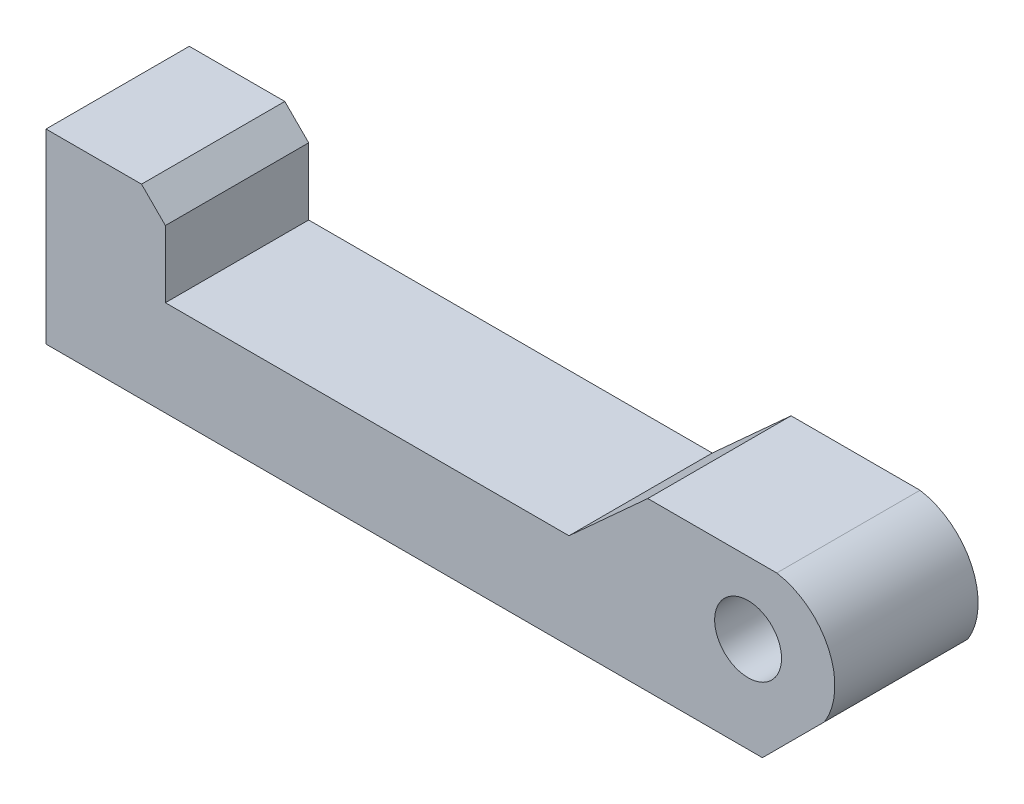
SolidWorks part; units mm, degrees
ref_plane "Front Plane" through (0, 0, 0) normal (0, 0, 1) x (1, 0, 0)
ref_plane "Top Plane" through (0, 0, 0) normal (0, 1, 0) x (1, 0, 0)
ref_plane "Right Plane" through (0, 0, 0) normal (1, 0, 0) x (0, 0, -1)
sketch "Sketch1" plane through (0, 0, 0) normal (0, 1, 0) x (1, 0, 0)
  line L1 (-8.15, -1.5) -> (8.15, -1.5)
  line L2 (-8.15, -1.5) -> (-8.15, 1.5)
  line L3 (-8.15, 1.5) -> (8.15, 1.5)
  line L4 (8.15, -1.5) -> (8.15, 1.5)
  line L5 (-8.15, -1.5) -> (8.15, 1.5) construction
  line L6 (-8.15, 1.5) -> (8.15, -1.5) construction
  point P0 (0, 0)
  dimension "D1" = 16.3
  dimension "D2" = 3
extrude "Boss-Extrude1" add sketch "Sketch1" along normal blind 2
sketch "Sketch2" plane through (0, 2, 0) normal (0, 1, 0) x (1, 0, 0)
  line L0 (-8.15, -1.5) -> (8.15, -1.5) construction
  line L1 (7.35, 1.5) -> (4.45, 1.5)
  line L2 (7.35, 1.5) -> (7.35, -1.5)
  line L3 (7.35, -1.5) -> (4.45, -1.5)
  line L4 (4.45, 1.5) -> (4.45, -1.5)
  line L5 (8.15, -1.5) -> (8.15, 1.5) construction
  dimension "D1" = 3.7
  dimension "D2" = 0.8
extrude "Boss-Extrude2" add sketch "Sketch2" along normal blind 1.5
sketch "Sketch6" plane through (0, 0, 1.5) normal (0, 0, 1) x (1, 0, 0)
  line L0 (4.45, 3.5) -> (2.8, 2)
  line L1 (-8.15, 2) -> (4.45, 2) construction
  line L2 (2.8, 2) -> (4.45, 2)
  line L3 (4.45, 2) -> (4.45, 3.5)
  line L10 (8.15, 2) -> (7.35, 2)
  line L11 (8.15, 2) -> (8.15, 3.5)
  line L12 (8.15, 3.5) -> (7.35, 3.5)
  line L13 (7.35, 2) -> (7.35, 3.5)
  dimension "D1" = 1.65
extrude "Boss-Extrude4" add sketch "Sketch6" against normal up to surface (3 mm away) up to face at (2.95, 1.875, -1.5)
hole_wizard "Ø1.4 (1.4) Diameter Hole1" positions "Sketch3" profile "Sketch4" hole size "Ø1.4" standard "DIN" end condition through all
sketch "Sketch3" plane through (0, 0, 1.5) normal (0, 0, 1) x (1, 0, 0)
  line L0 (-8.15, 0) -> (8.15, 0) construction
  line L1 (8.15, 3.5) -> (8.15, 0) construction
  point P0 (6.55, 2)
  dimension "D1" = 2
  dimension "D2" = 1.6
sketch "Sketch4" plane through (6.55, 2, 1.5) normal (1, 0, 0) x (0, -1, 0)
  line L0 (0, 0) -> (0, 3)
  line L1 (0, 3) -> (0.7, 3)
  line L2 (0.7, 3) -> (0.7, 0)
  line L5 (0.7, 0) -> (0, 0)
  line L11 (0, -6.35) -> (0, 107.95) construction
  dimension "Thru Hole Dia." = 1.4
  dimension "Thru Hole Depth" = 3
sketch "Sketch8" plane through (0, 0, 1.5) normal (0, 0, 1) x (1, 0, 0)
  line L0 (8.15, 0) -> (6.85, 0)
  line L1 (-8.15, 0) -> (8.15, 0) construction
  line L2 (6.85, 0) -> (8.15, 1.3)
  line L3 (8.15, 3.5) -> (8.15, 0) construction
  line L4 (8.15, 1.3) -> (8.15, 0)
  dimension "D1" = 1.3
  dimension "D2" = 1.3
extrude "Cut-Extrude1" cut sketch "Sketch8" against normal up to surface (3 mm away) up to face at (7.25, 2, -1.5)
sketch "Sketch9" plane through (0, 2, 0) normal (0, 1, 0) x (1, 0, 0)
  line L0 (2.8, 1.5) -> (-8.15, 1.5) construction
  line L1 (-8.15, -1.5) -> (-5.65, -1.5)
  line L2 (-8.15, -1.5) -> (-8.15, 1.5)
  line L3 (-8.15, 1.5) -> (-5.65, 1.5)
  line L4 (-5.65, -1.5) -> (-5.65, 1.5)
  dimension "D1" = 2.5
extrude "Boss-Extrude5" add sketch "Sketch9" along normal blind 1.9
sketch "Sketch10" plane through (0, 0, 1.5) normal (0, 0, 1) x (1, 0, 0)
  line L0 (-5.65, 3.9) -> (-5.65, 3.4)
  line L1 (-5.65, 3.9) -> (-5.65, 2) construction
  line L2 (-5.65, 3.4) -> (-6.15, 3.9)
  line L3 (-8.15, 3.9) -> (-5.65, 3.9) construction
  line L4 (-6.15, 3.9) -> (-5.65, 3.9)
  dimension "D1" = 0.5
  dimension "D2" = 0.5
extrude "Cut-Extrude2" cut sketch "Sketch10" against normal through all
sketch "Sketch13" plane through (0, 0, -1.5) normal (0, 0, -1) x (-1, 0, 0)
  line L0 (-8.15, 3.5) -> (-8.15, 2.5)
  line L1 (-8.15, 3.5) -> (-8.15, 1.3) construction
  line L2 (-8.15, 2.5) -> (-7.15, 3.5)
  line L3 (-8.15, 3.5) -> (-4.45, 3.5) construction
  line L4 (-7.15, 3.5) -> (-8.15, 3.5)
  dimension "D1" = 1
  dimension "D2" = 1
extrude "Cut-Extrude3" cut sketch "Sketch13" against normal blind 10
sketch "Sketch14" plane through (0, 0, -1.5) normal (0, 0, -1) x (-1, 0, 0)
  line L0 (-8.15, 1.3) -> (-7.15, 3.5)
  arc A0 (-8.15, 1.3) -> (-7.15, 3.5) centre (-6.9099, 2.0636) cw
extrude "Boss-Extrude7" add sketch "Sketch14" against normal up to surface (3 mm away) up to face at (7.25, 2, 1.5)
equation "\"D2@Sketch8\"=\"D1@Sketch8\""
equation "\"D2@Sketch10\"=\"D1@Sketch10\""
equation "\"D2@Sketch13\"=\"D1@Sketch13\""
